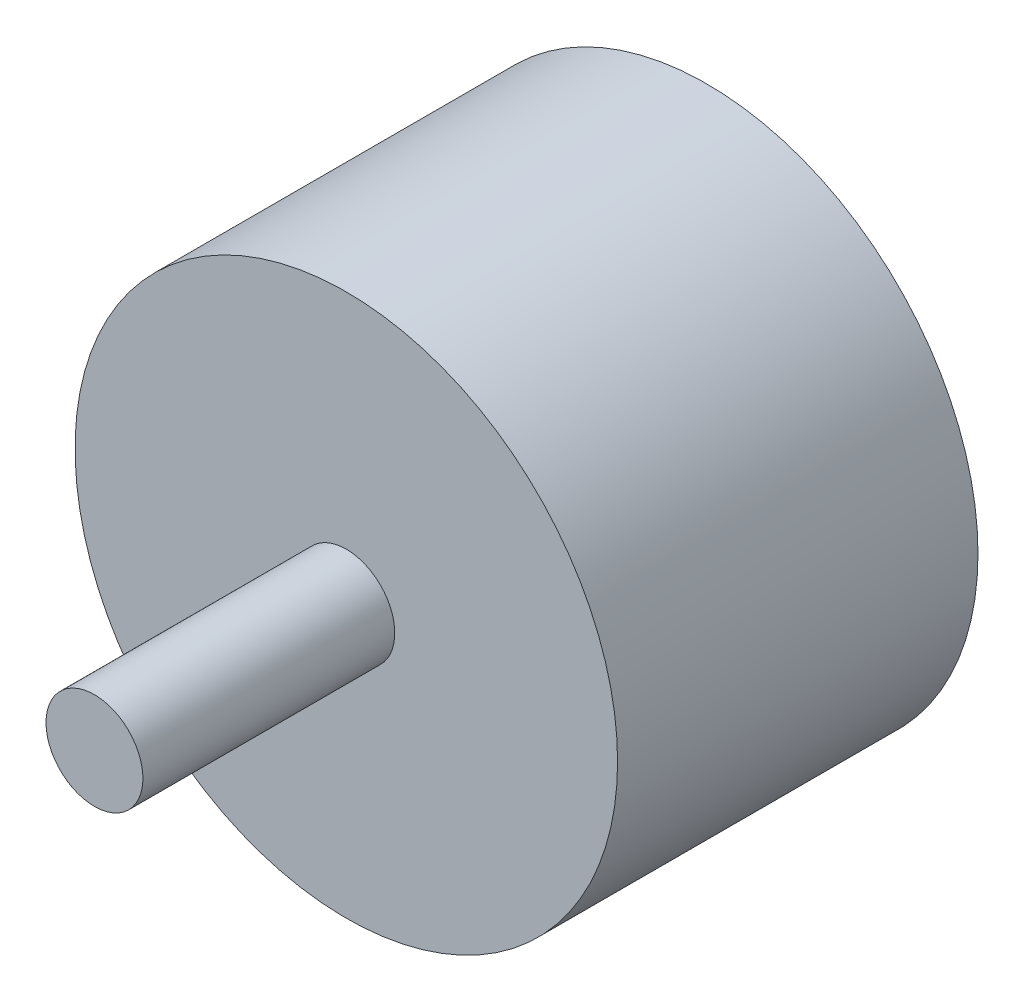
SolidWorks part; units mm, degrees
ref_plane "Front Plane" through (0, 0, 0) normal (0, 0, 1) x (1, 0, 0)
ref_plane "Top Plane" through (0, 0, 0) normal (0, 1, 0) x (1, 0, 0)
ref_plane "Right Plane" through (0, 0, 0) normal (1, 0, 0) x (0, 0, -1)
sketch "Sketch1" plane through (0, 0, 0) normal (0, 0, 1) x (1, 0, 0)
  circle A0 centre (0, 0) radius 14
  dimension "D1" = 28
extrude "Boss-Extrude1" add sketch "Sketch1" along normal blind 18.6 contours A0
sketch "Sketch2" plane through (0, 0, 18.6) normal (0, 0, 1) x (1, 0, 0)
  circle A0 centre (0, 0) radius 2.5
  dimension "D1" = 5
extrude "Boss-Extrude2" add sketch "Sketch2" along normal blind 13
